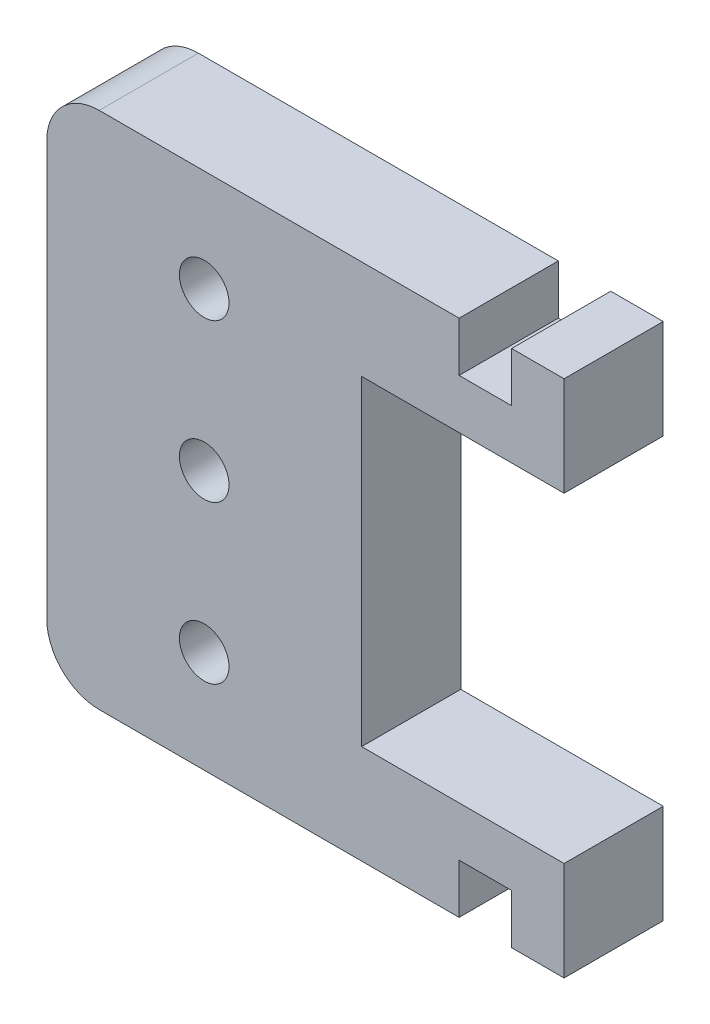
SolidWorks part; units mm, degrees
ref_plane "Front Plane" through (0, 0, 0) normal (0, 0, 1) x (1, 0, 0)
ref_plane "Top Plane" through (0, 0, 0) normal (0, 1, 0) x (1, 0, 0)
ref_plane "Right Plane" through (0, 0, 0) normal (1, 0, 0) x (0, 0, -1)
sketch "Sketch1" plane through (0, 0, 0) normal (0, 0, 1) x (1, 0, 0)
  line L0 (15.425, -15.7) -> (15.425, -12.7)
  line L1 (-9.525, -15.7) -> (9.525, -15.7)
  line L2 (-9.525, -15.7) -> (-9.525, 15.7)
  line L3 (-9.525, 15.7) -> (9.525, 15.7)
  line L4 (9.525, -15.7) -> (9.525, 15.7)
  line L5 (-9.525, -15.7) -> (9.525, 15.7) construction
  line L6 (-9.525, 15.7) -> (9.525, -15.7) construction
  line L7 (21.775, 9.7) -> (9.525, 9.7)
  line L8 (21.775, 9.7) -> (21.775, 15.7)
  line L9 (21.775, 15.7) -> (9.525, 15.7)
  line L10 (9.525, 9.7) -> (9.525, 15.7)
  line L11 (21.775, -9.7) -> (9.525, -9.7)
  line L12 (21.775, -9.7) -> (21.775, -15.7)
  line L13 (21.775, -15.7) -> (9.525, -15.7)
  line L14 (9.525, -9.7) -> (9.525, -15.7)
  line L15 (15.425, -12.7) -> (18.6, -12.7)
  line L16 (18.6, -12.7) -> (18.6, -15.7)
  line L17 (15.425, 15.7) -> (15.425, 12.7)
  line L18 (15.425, 12.7) -> (18.6, 12.7)
  line L19 (18.6, 12.7) -> (18.6, 15.7)
  point P0 (0, 0)
  dimension "D1" = 31.4
  dimension "D2" = 19.05
  dimension "D3" = 5.9
  dimension "D4" = 3.175
  dimension "D5" = 3.175
  dimension "D6" = 3
  dimension "D7" = 6
extrude "Boss-Extrude1" add sketch "Sketch1" along normal mid plane 6 contours L1 L4 L3 L2 | L19 L18 L17 L9 L4 L7 L8 | L15 L16 L13 L12 L11 L4 L0
fillet "Fillet1" radius 3.175 2 edges at (-9.525, -15.7, 0) (-9.525, 15.7, 0)
sketch "Sketch2" plane through (0, 0, 3) normal (0, 0, 1) x (1, 0, 0)
  line L0 (9.525, -9.7) -> (9.525, 9.7) construction
  line L1 (0, 9.525) -> (0, -9.525) construction
  circle A0 centre (0, 9.525) radius 1.5
  circle A1 centre (0, -9.525) radius 1.5
  circle A2 centre (0, 0) radius 1.5
  point P4 (0, 0)
  dimension "D1" = 3
  dimension "D2" = 9.525
  dimension "D3" = 19.05
extrude "Cut-Extrude1" cut sketch "Sketch2" against normal through all both and the other way through all
equation "\"D1@Sketch1\"=1in+6mm"
